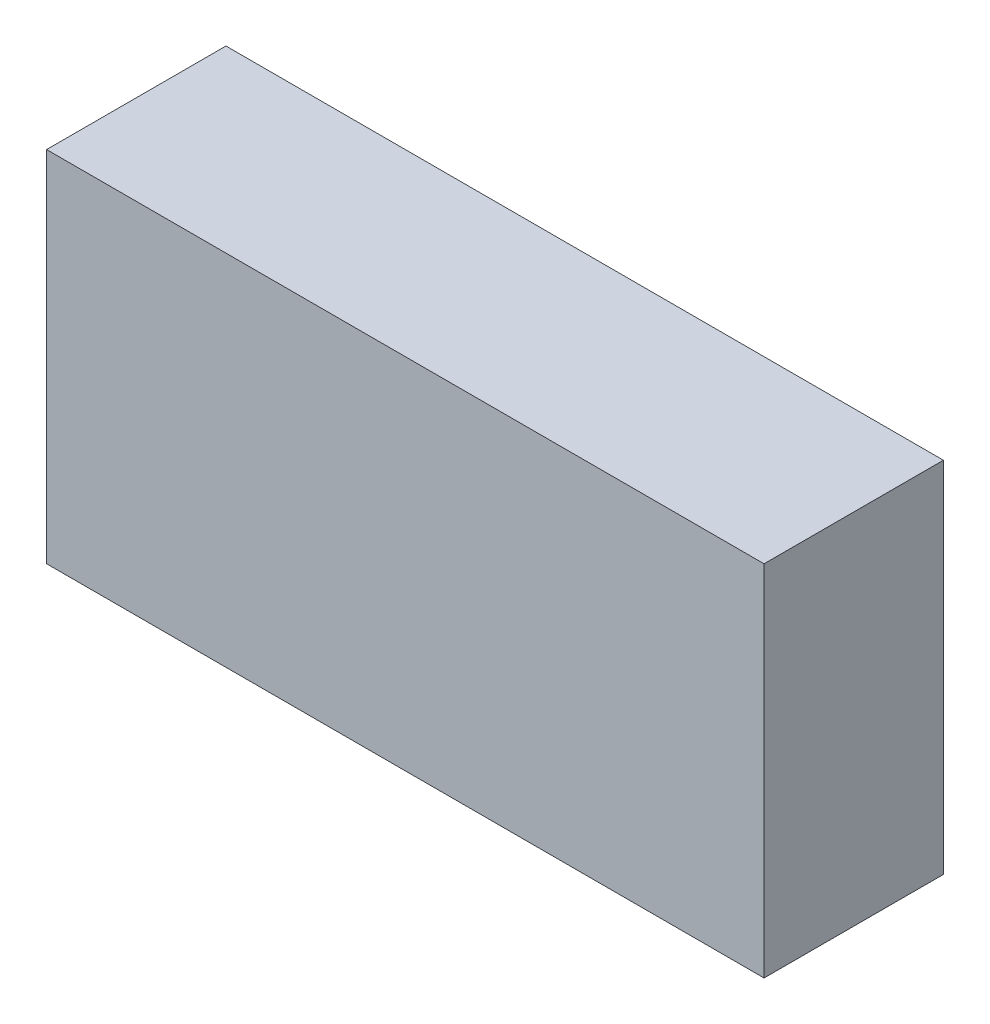
SolidWorks part; units mm, degrees
ref_plane "Front Plane" through (0, 0, 0) normal (0, 0, 1) x (1, 0, 0)
ref_plane "Top Plane" through (0, 0, 0) normal (0, 1, 0) x (1, 0, 0)
ref_plane "Right Plane" through (0, 0, 0) normal (1, 0, 0) x (0, 0, -1)
sketch "Sketch1" plane through (0, 0, 0) normal (0, 0, 1) x (1, 0, 0)
  line L0 (-2, 1) -> (2, 1)
  line L1 (2, 1) -> (2, -1)
  line L2 (2, -1) -> (-2, -1)
  line L3 (-2, -1) -> (-2, 1)
extrude "Component_Outline" add sketch "Sketch1" along normal blind 1 separate body
sketch3d "3DSketch1"
  line L0 (0, 0, 0) -> (1, 0, 0)
  line L1 (0, 0, 0) -> (0, 1, 0)
  line L2 (0, 0, 0) -> (0, 0, 1)
  point P0 (0, 0, 0)
